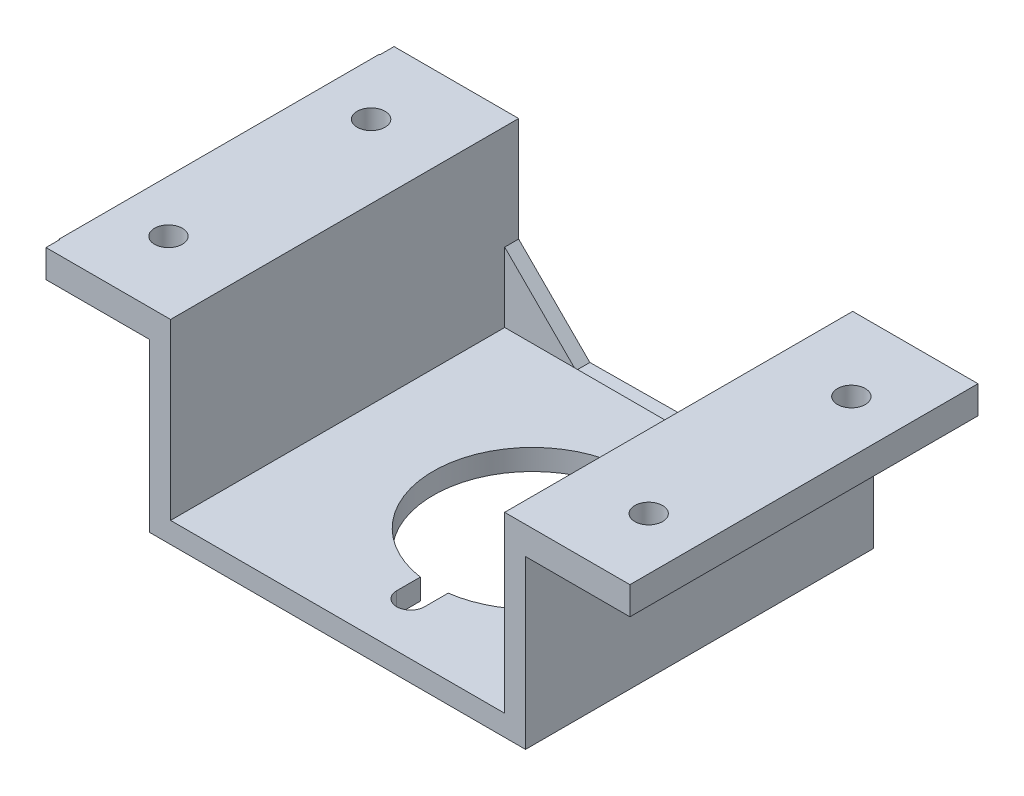
SolidWorks part; units mm, degrees
ref_plane "Front Plane" through (0, 0, 0) normal (0, 0, 1) x (1, 0, 0)
ref_plane "Top Plane" through (0, 0, 0) normal (0, 1, 0) x (1, 0, 0)
ref_plane "Right Plane" through (0, 0, 0) normal (1, 0, 0) x (0, 0, -1)
sketch "Sketch1" plane through (0, 0, 0) normal (0, 1, 0) x (1, 0, 0)
  line L1 (-23.0791, 14.3848) -> (26.9209, 14.3848)
  line L2 (-23.0791, 14.3848) -> (-23.0791, -25.6152)
  line L3 (-23.0791, -25.6152) -> (26.9209, -25.6152)
  line L4 (26.9209, 14.3848) -> (26.9209, -25.6152)
  dimension "D1" = 50
  dimension "D2" = 40
extrude "Boss-Extrude1" add sketch "Sketch1" along normal blind 3
sketch "Sketch2" plane through (0, 3, 0) normal (0, 1, 0) x (1, 0, 0)
  line L0 (-19.0791, 14.3848) -> (-19.0791, -25.6152)
  line L1 (26.9209, 14.3848) -> (-23.0791, 14.3848) construction
  line L2 (-23.0791, -25.6152) -> (26.9209, -25.6152) construction
  line L7 (-23.0791, 14.3848) -> (-23.0791, -25.6152)
  line L8 (-23.0791, -25.6152) -> (26.9209, -25.6152)
  line L9 (26.9209, -25.6152) -> (26.9209, 14.3848)
  line L10 (26.9209, 14.3848) -> (-23.0791, 14.3848)
  line L11 (-23.0791, 14.3848) -> (-23.0791, -25.6152)
  line L12 (-23.0791, -25.6152) -> (-19.0791, -25.6152)
  line L14 (-19.0791, 14.3848) -> (-23.0791, 14.3848)
  dimension "D1" = 0
  dimension "D2" = 4
sketch "Sketch5" plane through (0, 3, 0) normal (0, 1, 0) x (1, 0, 0)
  line L0 (24.9209, 14.3848) -> (24.9209, -25.6152)
  line L1 (26.9209, 14.3848) -> (-23.0791, 14.3848) construction
  line L2 (-23.0791, -25.6152) -> (26.9209, -25.6152) construction
  line L7 (-23.0791, 14.3848) -> (-23.0791, -25.6152)
  line L8 (-23.0791, -25.6152) -> (26.9209, -25.6152)
  line L9 (26.9209, -25.6152) -> (26.9209, 14.3848)
  line L10 (26.9209, 14.3848) -> (-23.0791, 14.3848)
  line L12 (24.9209, -25.6152) -> (26.9209, -25.6152)
  line L13 (26.9209, -25.6152) -> (26.9209, 14.3848)
  line L14 (26.9209, 14.3848) -> (24.9209, 14.3848)
  line L15 (-23.0791, 14.3848) -> (-23.0791, -25.6152)
  dimension "D1" = 0
  dimension "D2" = 2
sketch "Sketch6" plane through (0, 0, 0) normal (0, -1, 0) x (1, 0, 0)
  line L0 (-23.0791, 5.6152) -> (-1.0791, 5.6152)
  line L1 (-23.0791, -14.3848) -> (-23.0791, 25.6152) construction
  line L2 (6.9209, 5.6152) -> (6.9209, -11.8848)
  line L3 (-1.0791, 5.6152) -> (6.9209, 5.6152)
  line L4 (6.9209, 5.6152) -> (6.9209, 23.1152)
  line L5 (24.4209, 13.0152) -> (18.923, 13.0152)
  line L6 (6.9209, 5.6152) -> (24.4209, 5.6152)
  line L7 (24.4209, 5.6152) -> (24.4209, 13.0152)
  line L8 (24.4209, 5.6152) -> (24.4209, -1.7848)
  line L9 (24.4209, -1.7848) -> (18.923, -1.7848)
  arc A1 (18.923, 13.0152) -> (18.923, -1.7848) centre (6.9209, 5.6152) ccw
  circle A2 centre (6.9209, 23.1152) radius 2
  circle A3 centre (6.9209, -11.8848) radius 2
  dimension "D2" = 8
  dimension "D3" = 17.5
  dimension "D5" = 17.5
  dimension "D1" = 22
  dimension "D4" = 17.5
extrude "Cut-Extrude9" cut sketch "Sketch6" against normal blind 5
sketch "Sketch9" plane through (0, 0, 25.6152) normal (0, 0, 1) x (1, 0, 0)
sketch "Sketch16" plane through (24.4209, 0, 0) normal (-1, 0, 0) x (0, 0, 1)
  line L1 (13.0152, 0) -> (-1.7848, 0)
  line L2 (13.0152, 0) -> (13.0152, 3)
  line L3 (13.0152, 3) -> (-1.7848, 3)
  line L4 (-1.7848, 0) -> (-1.7848, 3)
extrude "Cut-Extrude10" cut sketch "Sketch16" against normal blind 0.5
sketch "Sketch21" plane through (0, 0, 0) normal (0, -1, 0) x (-1, 0, 0)
  circle A0 centre (-6.9209, -5.6152) radius 14.25
extrude "Cut-Extrude15" cut sketch "Sketch21" against normal blind 4
sketch "Sketch22" plane through (0, 3, 0) normal (0, 1, 0) x (1, 0, 0)
  line L0 (24.9209, 4.1848) -> (17.2661, 4.1848)
  line L1 (24.9209, -15.4152) -> (17.2661, -15.4152)
  line L2 (19.0989, 1.7848) -> (24.9209, 1.7848) construction
  line L3 (19.0989, -13.0152) -> (24.9209, -13.0152) construction
  circle A0 centre (6.9209, -5.6152) radius 15.9999
  arc A1 (19.0989, 1.7848) -> (19.0989, -13.0152) centre (6.9209, -5.6152) ccw construction
  arc M4 (19.0989, -13.0152) -> (19.0989, 1.7848) centre (6.9209, -5.6152) cw
  line M5 (19.0989, 1.7848) -> (24.9209, 1.7848)
  line M7 (24.9209, -13.0152) -> (19.0989, -13.0152)
  dimension "D1" = 2.4
  dimension "D2" = 2.4
extrude "Cut-Extrude16" cut sketch "Sketch22" against normal blind 4 contours A0 L0 M5 M4 | L1 A0 M7 M4
sketch "Sketch33" plane through (0, 3, 0) normal (0, 1, 0) x (1, 0, 0)
  line L0 (4.9209, 11.8848) -> (4.9209, -23.1152)
  line L1 (8.9209, -23.1152) -> (8.9209, 11.8848)
  line L2 (4.9209, 11.8848) -> (8.9209, 11.8848)
  line L3 (4.9209, -23.1152) -> (8.9209, -23.1152)
  circle A0 centre (6.9209, 11.8848) radius 2 construction
  circle A1 centre (6.9209, -23.1152) radius 2 construction
extrude "Cut-Extrude23" cut sketch "Sketch33" against normal blind 5
sketch "Sketch34" plane through (0, 0, -14.3848) normal (0, 0, -1) x (-1, 0, 0)
  line L0 (55, 0) -> (-55, 0) construction
  line L1 (-26.9209, 3) -> (23.066, 3)
  line L2 (-26.9209, 3) -> (-26.9209, 0)
  line L3 (-26.9209, 0) -> (23.066, 0)
  line L4 (23.066, 3) -> (23.066, 0)
extrude "Boss-Extrude2" add sketch "Sketch34" along normal blind 3
sketch "Sketch35" plane through (0, 0, 25.6152) normal (0, 0, 1) x (1, 0, 0)
  line L0 (55, 0) -> (-55, 0) construction
  line L1 (-23.0791, 3) -> (26.9209, 3)
  line L2 (-23.0791, 3) -> (-23.0791, 0)
  line L3 (-23.0791, 0) -> (26.9209, 0)
  line L4 (26.9209, 3) -> (26.9209, 0)
  line L5 (26.9209, 3) -> (26.9209, 0) construction
extrude "Boss-Extrude3" add sketch "Sketch35" along normal blind 3
sketch "Sketch36" plane through (26.9209, 0, 0) normal (1, 0, 0) x (0, 0, -1)
  line L0 (55, 0) -> (-55, 0) construction
  line L1 (-28.6152, 3) -> (17.3848, 3)
  line L2 (-28.6152, 3) -> (-28.6152, 0)
  line L3 (-28.6152, 0) -> (17.3848, 0)
  line L4 (17.3848, 3) -> (17.3848, 0)
  line L5 (17.3848, 3) -> (17.3848, 0) construction
extrude "Boss-Extrude4" add sketch "Sketch36" along normal blind 4
sketch "Sketch38" plane through (0, 3, 0) normal (0, 1, 0) x (1, 0, 0)
  line L0 (30.9209, -28.6152) -> (-23.0791, -28.6152) construction
  line L1 (30.9209, 17.3848) -> (27.9209, 17.3848)
  line L2 (30.9209, 17.3848) -> (30.9209, -28.6152)
  line L3 (30.9209, -28.6152) -> (27.9209, -28.6152)
  line L4 (27.9209, 17.3848) -> (27.9209, -28.6152)
  line L6 (-23.066, 17.3848) -> (-20.066, 17.3848)
  line L7 (-23.066, 17.3848) -> (-23.066, -28.6152)
  line L8 (-23.066, -28.6152) -> (-20.066, -28.6152)
  line L9 (-20.066, 17.3848) -> (-20.066, -28.6152)
  dimension "D1" = 3
  dimension "D2" = 3
extrude "Boss-Extrude5" add sketch "Sketch38" along normal blind 25
sketch "Sketch39" plane through (-23.066, 0, 0) normal (-1, 0, 0) x (0, 0, 1)
  line L1 (-17.3848, 28) -> (28.1507, 28)
  line L2 (-17.3848, 28) -> (-17.3848, 25)
  line L3 (-17.3848, 25) -> (28.1507, 25)
  line L4 (28.1507, 28) -> (28.1507, 25)
  dimension "D1" = 3
extrude "Boss-Extrude6" add sketch "Sketch39" along normal blind 15
sketch "Sketch40" plane through (30.9209, 0, 0) normal (1, 0, 0) x (0, 0, -1)
  line L0 (17.3848, 0) -> (17.3848, 28) construction
  line L1 (-28.6152, 28) -> (17.3848, 28)
  line L2 (-28.6152, 28) -> (-28.6152, 25)
  line L3 (-28.6152, 25) -> (17.3848, 25)
  line L4 (17.3848, 28) -> (17.3848, 25)
  dimension "D1" = 3
extrude "Boss-Extrude7" add sketch "Sketch40" along normal blind 15
sketch "Sketch41" plane through (-23.066, 0, 0) normal (-1, 0, 0) x (0, 0, 1)
  line L1 (28.6152, 28) -> (28.1507, 28)
  line L2 (28.6152, 28) -> (28.6152, 25)
  line L3 (28.6152, 25) -> (28.1507, 25)
  line L4 (28.1507, 28) -> (28.1507, 25)
extrude "Boss-Extrude8" add sketch "Sketch41" along normal blind 15
sketch "Sketch42" plane through (0, 25, 0) normal (0, -1, 0) x (1, 0, 0)
  line L0 (38.4209, 28.6152) -> (38.4209, -17.3848) construction
  line L1 (45.9209, 28.6152) -> (30.9209, 28.6152) construction
  line L2 (45.9209, -17.3848) -> (30.9209, -17.3848) construction
  line L3 (45.9209, 5.6152) -> (30.9209, -17.3848) construction
  line L4 (45.9209, 28.6152) -> (45.9209, -17.3848) construction
  line L5 (30.9209, 28.6152) -> (45.9209, 5.6152) construction
  line L6 (45.9209, 28.6152) -> (30.9209, 12.2239) construction
  line L7 (30.9209, 28.6152) -> (30.9209, -17.3848) construction
  line L8 (45.9209, -17.3848) -> (30.9209, 0) construction
  line L9 (44.2539, 0) -> (-44.2539, 0) construction
  circle A0 centre (38.4209, 20.4195) radius 2
  circle A2 centre (38.4209, -8.6924) radius 2
  dimension "D1" = 4
  dimension "D2" = 4
extrude "Cut-Extrude24" cut sketch "Sketch42" against normal blind 15 contours A0 | A2
sketch "Sketch43" plane through (0, 25, 0) normal (0, -1, 0) x (1, 0, 0)
  line L0 (-30.566, 28.6152) -> (-30.566, -17.3848) construction
  line L1 (-38.066, 28.6152) -> (-23.066, 28.6152) construction
  line L2 (-38.066, -17.3848) -> (-23.066, -17.3848) construction
  line L3 (40.4209, 20.4195) -> (-49.3024, 20.4195) construction
  line L4 (40.4209, -8.6924) -> (-52.4667, -8.6924) construction
  circle A0 centre (38.4209, 20.4195) radius 2 construction
  circle A1 centre (38.4209, -8.6924) radius 2 construction
  circle A2 centre (-30.566, 20.4195) radius 2
  circle A3 centre (-30.566, -8.6924) radius 2
  dimension "D1" = 4
extrude "Cut-Extrude25" cut sketch "Sketch43" against normal blind 15
sketch "Sketch44" plane through (0, 25, 0) normal (0, -1, 0) x (1, 0, 0)
  line L1 (-23.0791, 28.6152) -> (-38.066, 28.6152)
  line L2 (-23.0791, 28.6152) -> (-23.0791, -17.3848)
  line L3 (-23.0791, -17.3848) -> (-38.066, -17.3848)
  line L4 (-38.066, 28.6152) -> (-38.066, -17.3848)
  line L8 (-23.066, -17.3848) -> (-23.066, 28.6152)
  line L9 (-23.066, 28.6152) -> (-38.066, 28.6152)
  line L10 (-38.066, 28.6152) -> (-38.066, -17.3848)
  line L11 (-38.066, -17.3848) -> (-23.066, -17.3848)
  line L12 (-23.066, -17.3848) -> (-23.066, 28.6152)
  line L13 (-23.066, 28.6152) -> (-38.066, 28.6152)
  line L14 (-38.066, 28.6152) -> (-38.066, -17.3848)
  line L15 (-38.066, -17.3848) -> (-23.066, -17.3848)
  circle M9 centre (-30.566, 20.4195) radius 2
  circle M10 centre (-30.566, -8.6924) radius 2
  line M12 (-23.066, 28.6152) -> (-38.066, 28.6152)
  line M13 (-38.066, 28.6152) -> (-38.066, -17.3848)
  line M14 (-38.066, -17.3848) -> (-23.066, -17.3848)
  dimension "D1" = 0
extrude "Boss-Extrude10" add sketch "Sketch44" along normal blind 1 contours L2 M12 M13 M14 M10 M9
sketch "Sketch46" plane through (0, 25, 0) normal (0, -1, 0) x (1, 0, 0)
  line L1 (45.9209, 28.6152) -> (30.9209, 28.6152)
  line L2 (45.9209, 28.6152) -> (45.9209, -17.3848)
  line L3 (45.9209, -17.3848) -> (30.9209, -17.3848)
  line L4 (30.9209, 28.6152) -> (30.9209, -17.3848)
  line L8 (30.9209, 28.6152) -> (30.9209, -17.3848)
  line L9 (30.9209, -17.3848) -> (45.9209, -17.3848)
  line L10 (45.9209, -17.3848) -> (45.9209, 28.6152)
  line L11 (45.9209, 28.6152) -> (30.9209, 28.6152)
  line L12 (30.9209, 28.6152) -> (30.9209, -17.3848)
  line L13 (30.9209, -17.3848) -> (45.9209, -17.3848)
  line L14 (45.9209, -17.3848) -> (45.9209, 28.6152)
  line L15 (45.9209, 28.6152) -> (30.9209, 28.6152)
  line L16 (45.9209, 28.6152) -> (27.9209, 28.6152)
  line L17 (45.9209, -17.3848) -> (45.9209, 28.6152)
  line L18 (27.9209, -17.3848) -> (45.9209, -17.3848)
  line L19 (27.9209, 28.6152) -> (27.9209, -17.3848)
  line L20 (45.9209, 28.6152) -> (27.9209, 28.6152)
  line L21 (45.9209, -17.3848) -> (45.9209, 28.6152)
  line L22 (27.9209, -17.3848) -> (45.9209, -17.3848)
  line L23 (27.9209, 28.6152) -> (27.9209, -17.3848)
  circle M13 centre (38.4209, 20.4195) radius 2
  circle M14 centre (38.4209, -8.6924) radius 2
  line M15 (30.9209, 28.6152) -> (30.9209, -17.3848)
  line M16 (30.9209, -17.3848) -> (45.9209, -17.3848)
  line M17 (45.9209, -17.3848) -> (45.9209, 28.6152)
  line M18 (45.9209, 28.6152) -> (30.9209, 28.6152)
  dimension "D1" = 0
  dimension "D2" = 0
extrude "Boss-Extrude11" add sketch "Sketch46" along normal blind 1 contours M18 M15 M16 M17 M14 M13
sketch "Sketch47" plane through (0, 0, -17.3848) normal (0, 0, -1) x (-1, 0, 0)
  line L0 (55, 0) -> (-55, 0) construction
  line L1 (-45.9209, 28) -> (37.9603, 28)
  line L2 (-45.9209, 28) -> (-45.9209, 0)
  line L3 (-45.9209, 0) -> (37.9603, 0)
  line L4 (37.9603, 28) -> (37.9603, 0)
  line L19 (23.066, 0) -> (23.066, 25)
  line L20 (23.066, 25) -> (23.0791, 25)
  line L21 (-30.9209, 24) -> (-30.9209, 0)
  line L22 (-45.9209, 24) -> (-30.9209, 24)
  line L23 (-45.9209, 28) -> (-45.9209, 24)
  line L24 (-27.9209, 28) -> (-45.9209, 28)
  line L25 (-27.9209, 3) -> (-27.9209, 28)
  line L26 (20.066, 3) -> (-27.9209, 3)
  line L27 (20.066, 28) -> (20.066, 3)
  line L28 (38.066, 28) -> (20.066, 28)
  line L29 (38.066, 24) -> (38.066, 28)
  line L30 (23.0791, 24) -> (38.066, 24)
  line L31 (23.0791, 25) -> (23.0791, 24)
  line L32 (23.066, 25) -> (23.0791, 25)
  line L33 (23.066, 3) -> (23.066, 25)
  line L34 (23.0791, 3) -> (23.066, 3)
  line L35 (23.0791, 0) -> (23.0791, 3)
  line L36 (-30.9209, 0) -> (23.0791, 0)
  line L37 (-30.9209, 24) -> (-30.9209, 0)
  line L38 (-45.9209, 24) -> (-30.9209, 24)
  line L39 (-45.9209, 28) -> (-45.9209, 24)
  line L40 (-27.9209, 28) -> (-45.9209, 28)
  line L41 (-27.9209, 3) -> (-27.9209, 28)
  line L42 (20.066, 3) -> (-27.9209, 3)
  line L43 (20.066, 28) -> (20.066, 3)
  line L44 (38.066, 28) -> (20.066, 28)
  line L45 (38.066, 24) -> (38.066, 28)
  line L46 (23.0791, 24) -> (38.066, 24)
  line L47 (23.0791, 25) -> (23.0791, 24)
  line L48 (23.066, 25) -> (23.0791, 25)
  line L49 (23.066, 3) -> (23.066, 25)
  line L50 (23.0791, 3) -> (23.066, 3)
  line L51 (23.0791, 0) -> (23.0791, 3)
  line L52 (-30.9209, 0) -> (23.0791, 0)
  line L53 (23.0791, 25) -> (23.0791, 24)
  line L54 (23.0791, 24) -> (38.066, 24)
  line L55 (38.066, 24) -> (38.066, 28)
  line L56 (38.066, 28) -> (20.066, 28)
  line L57 (20.066, 28) -> (20.066, 3)
  line L58 (20.066, 3) -> (-27.9209, 3)
  line L59 (-27.9209, 3) -> (-27.9209, 28)
  line L60 (-27.9209, 28) -> (-45.9209, 28)
  line L61 (-45.9209, 28) -> (-45.9209, 24)
  line L62 (-45.9209, 24) -> (-30.9209, 24)
  line L63 (-30.9209, 24) -> (-30.9209, 0)
  line L64 (-30.9209, 0) -> (23.066, 0)
  line L65 (23.066, 0) -> (23.066, 25)
  line L66 (23.066, 25) -> (23.0791, 25)
  line L67 (23.0791, 25) -> (23.0791, 24)
  line L68 (23.0791, 24) -> (38.066, 24)
  line L69 (38.066, 24) -> (38.066, 28)
  line L70 (38.066, 28) -> (20.066, 28)
  line L71 (20.066, 28) -> (20.066, 3)
  line L72 (20.066, 3) -> (-27.9209, 3)
  line L73 (-27.9209, 3) -> (-27.9209, 28)
  line L74 (-27.9209, 28) -> (-45.9209, 28)
  line L75 (-45.9209, 28) -> (-45.9209, 24)
  line L76 (-45.9209, 24) -> (-30.9209, 24)
  line L77 (-30.9209, 24) -> (-30.9209, 0)
  line L78 (-30.9209, 0) -> (23.066, 0)
  line M35 (23.066, 0) -> (23.066, 25)
  line M36 (23.066, 25) -> (23.0791, 25)
  line M37 (23.0791, 25) -> (23.0791, 24)
  line M38 (23.0791, 24) -> (38.066, 24)
  line M40 (38.066, 28) -> (20.066, 28)
  line M41 (20.066, 28) -> (20.066, 3)
  line M42 (20.066, 3) -> (-27.9209, 3)
  line M43 (-27.9209, 3) -> (-27.9209, 28)
  line M44 (-27.9209, 28) -> (-45.9209, 28)
  line M45 (-45.9209, 28) -> (-45.9209, 24)
  line M46 (-45.9209, 24) -> (-30.9209, 24)
  line M47 (-30.9209, 24) -> (-30.9209, 0)
  line M48 (-30.9209, 0) -> (23.066, 0)
  dimension "D1" = 0
  dimension "D2" = 0
extrude "Boss-Extrude12" add sketch "Sketch47" along normal blind 2 contours L4 M40 M41 M42 M43 M44 M45 M46 M47 M48 M35 M36 M37 M38
sketch "Sketch48" plane through (0, 0, 28.6152) normal (0, 0, 1) x (1, 0, 0)
  line L0 (55, 0) -> (-55, 0) construction
  line L1 (-38.066, 28) -> (45.9209, 28)
  line L2 (-38.066, 28) -> (-38.066, 0)
  line L3 (-38.066, 0) -> (45.9209, 0)
  line L4 (45.9209, 28) -> (45.9209, 0)
  line L19 (-37.9603, 28) -> (-37.9603, 24)
  line L20 (-20.066, 28) -> (-37.9603, 28)
  line L21 (-20.066, 3) -> (-20.066, 28)
  line L22 (27.9209, 3) -> (-20.066, 3)
  line L23 (27.9209, 28) -> (27.9209, 3)
  line L24 (45.9209, 28) -> (27.9209, 28)
  line L25 (45.9209, 24) -> (45.9209, 28)
  line L26 (30.9209, 24) -> (45.9209, 24)
  line L27 (30.9209, 0) -> (30.9209, 24)
  line L28 (-23.066, 0) -> (30.9209, 0)
  line L29 (-23.066, 25) -> (-23.066, 0)
  line L30 (-23.0791, 25) -> (-23.066, 25)
  line L31 (-23.0791, 24) -> (-23.0791, 25)
  line L32 (-37.9603, 24) -> (-23.0791, 24)
  line L33 (-37.9603, 28) -> (-37.9603, 24)
  line L34 (-20.066, 28) -> (-37.9603, 28)
  line L35 (-20.066, 3) -> (-20.066, 28)
  line L36 (27.9209, 3) -> (-20.066, 3)
  line L37 (27.9209, 28) -> (27.9209, 3)
  line L38 (45.9209, 28) -> (27.9209, 28)
  line L39 (45.9209, 24) -> (45.9209, 28)
  line L40 (30.9209, 24) -> (45.9209, 24)
  line L41 (30.9209, 0) -> (30.9209, 24)
  line L42 (-23.066, 0) -> (30.9209, 0)
  line L43 (-23.066, 25) -> (-23.066, 0)
  line L44 (-23.0791, 25) -> (-23.066, 25)
  line L45 (-23.0791, 24) -> (-23.0791, 25)
  line L46 (-37.9603, 24) -> (-23.0791, 24)
  line M19 (30.9209, 0) -> (30.9209, 24)
  line M20 (30.9209, 24) -> (45.9209, 24)
  line M21 (45.9209, 24) -> (45.9209, 28)
  line M22 (45.9209, 28) -> (27.9209, 28)
  line M23 (27.9209, 28) -> (27.9209, 3)
  line M24 (27.9209, 3) -> (-20.066, 3)
  line M25 (-20.066, 3) -> (-20.066, 28)
  line M26 (-20.066, 28) -> (-38.066, 28)
  line M28 (-38.066, 24) -> (-23.0791, 24)
  line M29 (-23.0791, 24) -> (-23.0791, 25)
  line M30 (-23.0791, 25) -> (-23.066, 25)
  line M31 (-23.066, 25) -> (-23.066, 3)
  dimension "D1" = 0
extrude "Boss-Extrude13" add sketch "Sketch48" along normal blind 2 contours L43 L3 L33 M31 M19 M20 M21 M22 M23 M24 M25 M26 M28 M29 M30
sketch "Sketch49" plane through (0, 3, 0) normal (0, 1, 0) x (1, 0, 0)
  line L0 (27.9209, 19.3848) -> (27.9209, -30.6152) construction
  line L1 (-20.066, 19.3848) -> (27.9209, 19.3848)
  line L2 (-20.066, 19.3848) -> (-20.066, 17.3848)
  line L3 (-20.066, 17.3848) -> (27.9209, 17.3848)
  line L4 (27.9209, 19.3848) -> (27.9209, 17.3848)
  dimension "D1" = 2
extrude "Boss-Extrude14" add sketch "Sketch49" along normal blind 10
sketch "Sketch50" plane through (0, 0, -17.3848) normal (0, 0, 1) x (1, 0, 0)
  line L0 (-20.066, 13) -> (-9.8306, 2.7646)
  line L1 (27.9209, 13) -> (17.9209, 3)
  line L2 (-20.066, 3) -> (27.9209, 3) construction
  line L3 (27.9209, 13) -> (-20.066, 13)
  line L4 (-9.8306, 2.7646) -> (17.9209, 3)
extrude "Cut-Extrude26" cut sketch "Sketch50" against normal blind 10
